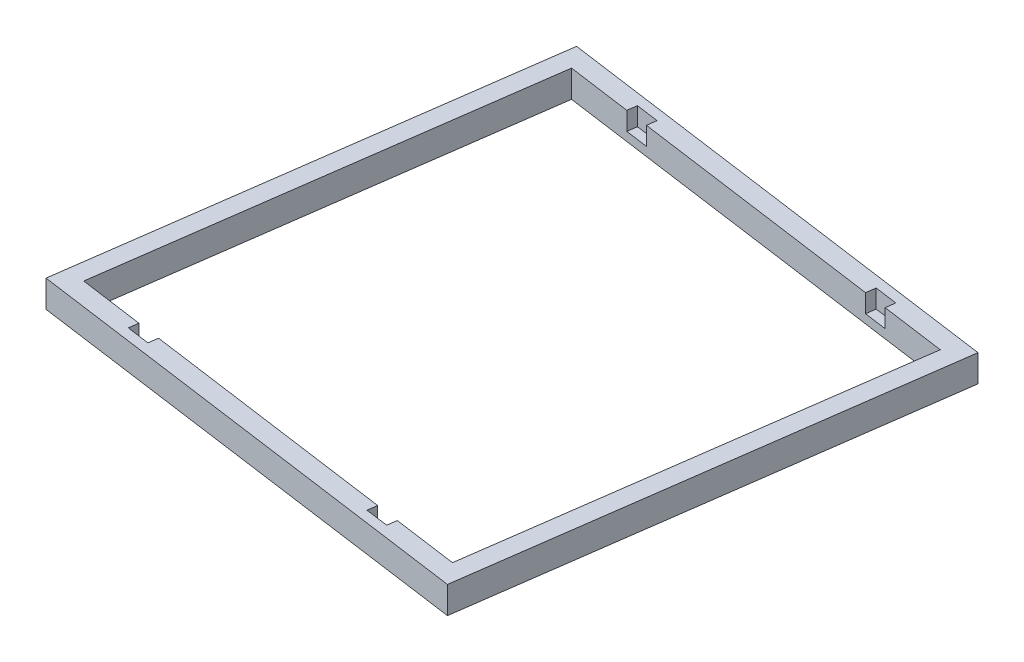
SolidWorks part; units mm, degrees
ref_plane "Front Plane" through (0, 0, 0) normal (0, 0, 1) x (1, 0, 0)
ref_plane "Top Plane" through (0, 0, 0) normal (0, 1, 0) x (1, 0, 0)
ref_plane "Right Plane" through (0, 0, 0) normal (1, 0, 0) x (0, 0, -1)
sketch "Sketch1" plane through (0, 0, 0) normal (0, 1, 0) x (1, 0, 0)
  line L1 (-28.9178, -24.4138) -> (-16.7917, 63.1084)
  line L2 (-16.7917, 63.1084) -> (-104.3139, 75.2345)
  line L3 (-104.3139, 75.2345) -> (-116.44, -12.2877)
  line L4 (-116.44, -12.2877) -> (-28.9178, -24.4138)
  line L5 (-20.8067, 60.0394) -> (-101.2449, 71.2196)
  line L6 (-101.2449, 71.2196) -> (-112.4251, -9.2187)
  line L7 (-112.4251, -9.2187) -> (-31.9868, -20.3989)
  line L8 (-31.9868, -20.3989) -> (-20.8067, 60.0394)
  circle A0 centre (-66.6159, 25.4103) radius 44.1791 construction
  circle A1 centre (-66.6159, 25.4103) radius 40.6058 construction
extrude "Boss-Extrude1" add sketch "Sketch1" along normal blind 5.08
sketch "Sketch9" plane through (-3.3878, 0, 24.3739) normal (0.1377, 0, -0.9905) x (-0.9905, 0, -0.1377)
  line L1 (41.021, 1.651) -> (45.339, 1.651)
  line L2 (45.339, 1.651) -> (45.339, 5.969)
  line L3 (45.339, 5.969) -> (41.021, 5.969)
  line L4 (41.021, 5.969) -> (41.021, 1.651)
  circle A0 centre (43.18, 3.81) radius 2.159 construction
extrude "Cut-Extrude3" cut sketch "Sketch9" against normal blind 1.778
sketch "Sketch10" plane through (7.7924, 0, -56.0644) normal (-0.1377, 0, 0.9905) x (0.9905, 0, 0.1377)
  line L1 (-41.021, 5.969) -> (-45.339, 5.969)
  line L2 (-45.339, 5.969) -> (-45.339, 1.651)
  line L3 (-45.339, 1.651) -> (-41.021, 1.651)
  line L4 (-41.021, 1.651) -> (-41.021, 5.969)
  circle A0 centre (-43.18, 3.81) radius 2.159 construction
extrude "Cut-Extrude4" cut sketch "Sketch10" against normal blind 1.778
sketch "Sketch11" plane through (7.7924, 0, -56.0644) normal (-0.1377, 0, 0.9905) x (0.9905, 0, 0.1377)
  line L1 (-93.599, 5.969) -> (-97.917, 5.969)
  line L2 (-97.917, 5.969) -> (-97.917, 1.651)
  line L3 (-97.917, 1.651) -> (-93.599, 1.651)
  line L4 (-93.599, 1.651) -> (-93.599, 5.969)
  circle A0 centre (-95.758, 3.81) radius 2.159 construction
extrude "Cut-Extrude5" cut sketch "Sketch11" against normal blind 1.778
sketch "Sketch12" plane through (-3.3878, 0, 24.3739) normal (0.1377, 0, -0.9905) x (-0.9905, 0, -0.1377)
  line L1 (93.599, 1.651) -> (97.917, 1.651)
  line L2 (97.917, 1.651) -> (97.917, 5.969)
  line L3 (97.917, 5.969) -> (93.599, 5.969)
  line L4 (93.599, 5.969) -> (93.599, 1.651)
  circle A0 centre (95.758, 3.81) radius 2.159 construction
extrude "Cut-Extrude6" cut sketch "Sketch12" against normal blind 1.778
